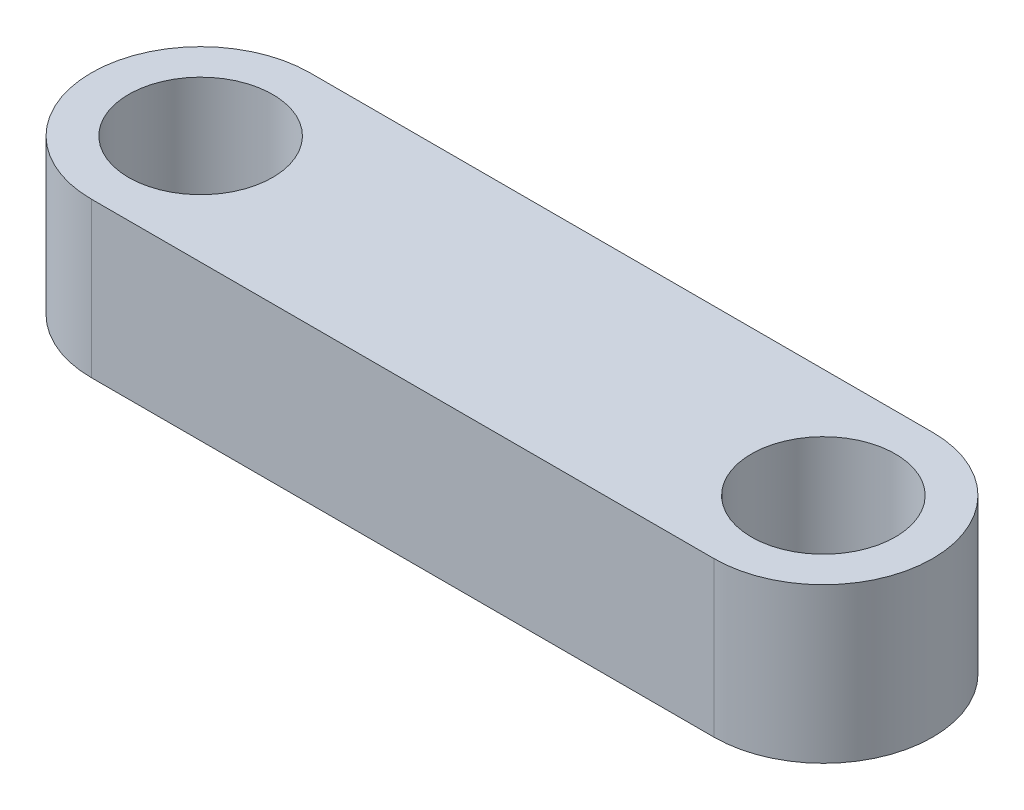
SolidWorks part; units mm, degrees
ref_plane "Alzado" through (0, 0, 0) normal (0, 0, 1) x (1, 0, 0)
ref_plane "Planta" through (0, 0, 0) normal (0, 1, 0) x (1, 0, 0)
ref_plane "Vista lateral" through (0, 0, 0) normal (1, 0, 0) x (0, 0, -1)
sketch "Sketch1" plane through (0, 0, 0) normal (0, 1, 0) x (1, 0, 0)
  line L0 (-11.675, 0) -> (11.675, 0) construction
  line L1 (-11.675, 4.1) -> (11.675, 4.1)
  line L2 (-11.675, -4.1) -> (11.675, -4.1)
  arc A0 (-11.675, 4.1) -> (-11.675, -4.1) centre (-11.675, 0) ccw
  arc A1 (11.675, -4.1) -> (11.675, 4.1) centre (11.675, 0) ccw
  circle A2 centre (-11.675, 0) radius 2.7
  circle A3 centre (11.675, 0) radius 2.7
  point P2 (0, 0)
  dimension "D3" = 5.4
  dimension "D1" = 8.2
  dimension "D2" = 23.35
extrude "Boss-Extrude1" add sketch "Sketch1" along normal blind 5.8
